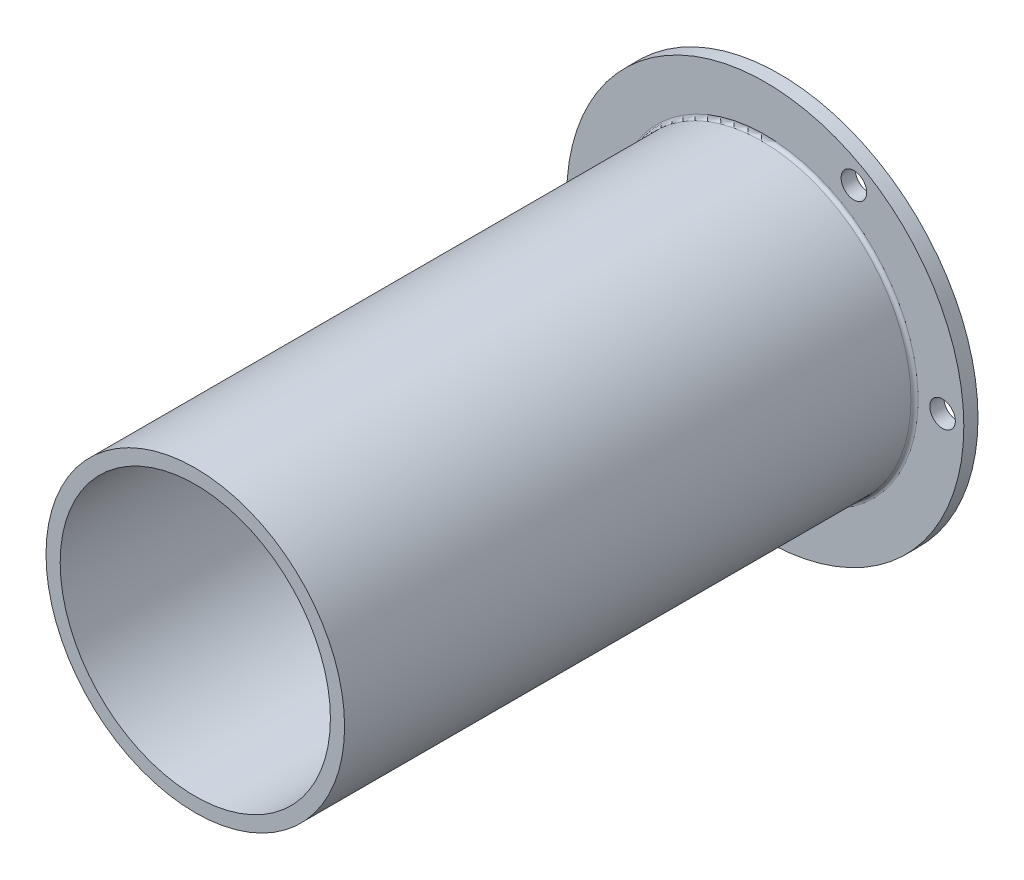
SolidWorks part; units mm, degrees
material "6061-T6 (SS)"
ref_plane "Front Plane" through (0, 0, 0) normal (0, 0, 1) x (1, 0, 0)
ref_plane "Top Plane" through (0, 0, 0) normal (0, 1, 0) x (1, 0, 0)
ref_plane "Right Plane" through (0, 0, 0) normal (1, 0, 0) x (0, 0, -1)
sketch "Sketch1" plane through (0, 0, 0) normal (0, 0, 1) x (1, 0, 0)
  circle A0 centre (0, 0) radius 9.525
  circle A1 centre (0, 0) radius 10.525
  dimension "D1" = 19.05
  dimension "D2" = 21.05
extrude "Boss-Extrude1" add sketch "Sketch1" along normal blind 40.18
sketch "Sketch2" plane through (0, 0, 0) normal (0, 0, -1) x (-1, 0, 0)
  circle A0 centre (0, 0) radius 14
  circle A1 centre (0, 0) radius 9.525 construction
  circle A2 centre (0, 0) radius 9.525
  dimension "D1" = 28
  dimension "D2" = 0
extrude "Boss-Extrude2" add sketch "Sketch2" along normal blind 1
hole_wizard "M1.6 Clearance Hole1" positions "Sketch10" profile "Sketch11" hole size "M1.6" standard "ISO"
sketch "Sketch10" plane through (0, 0, 0) normal (0, 0, 1) x (1, 0, 0)
  point P0 (-12.5, 0)
  dimension "D1" = 12.5
sketch "Sketch11" plane through (-12.5, 0, 0) normal (1, 0, 0) x (0, -1, 0)
  line L0 (0, 0) -> (0, 5.5408)
  line L1 (0, 5.5408) -> (0.9, 5)
  line L2 (0.9, 5) -> (0.9, 0)
  line L5 (0.9, 0) -> (0, 0)
  line L10 (0, 5.5408) -> (-0.9, 5) construction
  line L11 (0, -6.35) -> (0, 107.95) construction
  dimension "Hole Dia." = 1.8
  dimension "Hole Depth" = 5
  dimension "Drill Angle" = 118
pattern_circular "CirPattern1" count 6 over 360 about axis through (0, 0, 0) along (0, 0, -1) skipping 1, 4 of "M1.6 Clearance Hole1"
fillet "Fillet1" radius 0.25 1 edges at (10.525, 0, 0)
